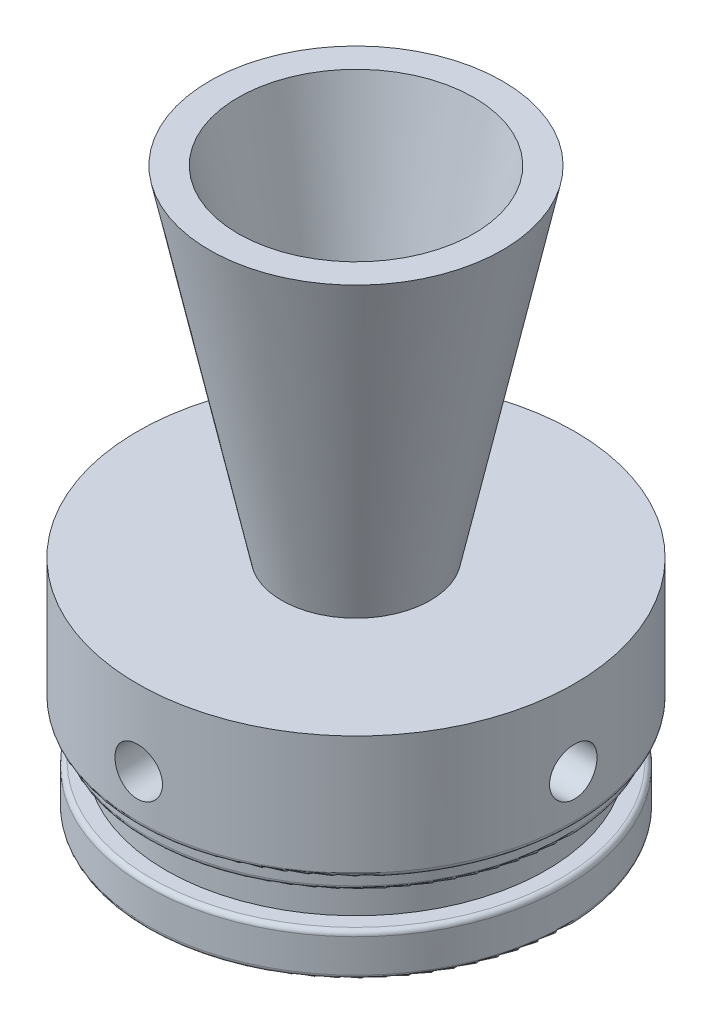
SolidWorks part; units mm, degrees
material "보통 탄소강"
ref_plane "정면" through (0, 0, 0) normal (0, 0, 1) x (1, 0, 0)
ref_plane "윗면" through (0, 0, 0) normal (0, 1, 0) x (1, 0, 0)
ref_plane "우측면" through (0, 0, 0) normal (1, 0, 0) x (0, 0, -1)
sketch "스케치1" plane through (0, 0, 0) normal (0, 0, 1) x (1, 0, 0)
  line L8 (0, 0) -> (0, 58.72)
  line L9 (0, 58.72) -> (12.41, 58.72)
  line L10 (12.41, 58.72) -> (4.605, 21.99)
  line L11 (4.605, 21.99) -> (20, 0)
  line L12 (20, 0) -> (0, 0)
  line L13 (4.605, 21.99) -> (0, 21.99)
  line L14 (0, 0) -> (0, 58.72)
  line L15 (12.41, 58.72) -> (15.41, 58.72)
  line L16 (15.41, 58.72) -> (7.8196, 23)
  line L17 (7.8196, 23) -> (23, 23)
  line L18 (23, 23) -> (23, 10)
  line L19 (23, 10) -> (22, 10)
  line L20 (22, 10) -> (22, 0)
  line L21 (22, 0) -> (20, 0)
  line L22 (22, 10) -> (22, 8)
  line L23 (22, 8) -> (20, 8)
  line L24 (20, 8) -> (20, 4.5)
  line L25 (20, 4.5) -> (22, 4.5)
  line L26 (22, 4.5) -> (22, 0)
  line L27 (20, 0) -> (22, 0)
  line L28 (20, 8) -> (22, 8.175)
  dimension "D1" = 58.72
  dimension "D2" = 4.605
  dimension "D3" = 20
  dimension "D4" = 12.41
  dimension "D5" = 21.99
  dimension "D6" = 3
  dimension "D7" = 2
  dimension "D8" = 1
  dimension "D9" = 10
  dimension "D10" = 13
  dimension "D11" = 2
  dimension "D12" = 2
  dimension "D13" = 3.5
revolve "회전2" add sketch "스케치1" angle 360 about L8
fillet "필렛3" radius 0.5 1 edges at (0, 8.175, -22)
fillet "필렛4" radius 0.5 1 edges at (0, 4.5, -22)
ref_plane "평면1" through (-23, 0, 0) normal (-1, 0, 0) x (0, 0, 1)
sketch "스케치4" plane through (-23, 0, 0) normal (-1, 0, 0) x (0, 0, 1)
  line L0 (0, 10) -> (0, 15)
  line L1 (-22, 10) -> (22, 10) construction
  circle A0 centre (0, 15) radius 2.5
  dimension "D1" = 5
extrude "컷-돌출1" cut sketch "스케치4" against normal blind 6
ref_plane "평면2" through (0, 0, 23) normal (0, 0, 1) x (1, 0, 0)
sketch "스케치5" plane through (0, 0, 23) normal (0, 0, 1) x (1, 0, 0)
  line L0 (0, 10) -> (0, 15)
  line L1 (-22, 10) -> (22, 10) construction
  circle A0 centre (0, 15) radius 2.5
  dimension "D1" = 5
extrude "컷-돌출2" cut sketch "스케치5" against normal blind 6
ref_plane "평면3" through (23, 0, 0) normal (1, 0, 0) x (0, 0, -1)
sketch "스케치6" plane through (23, 0, 0) normal (1, 0, 0) x (0, 0, -1)
  line L0 (0, 10) -> (0, 15)
  line L1 (-22, 10) -> (22, 10) construction
  circle A0 centre (0, 15) radius 2.5
  dimension "D1" = 5
extrude "컷-돌출3" cut sketch "스케치6" against normal blind 6
ref_plane "평면4" through (0, 0, -23) normal (0, 0, -1) x (-1, 0, 0)
sketch "스케치7" plane through (0, 0, -23) normal (0, 0, -1) x (-1, 0, 0)
  line L0 (0, 10) -> (0, 15)
  line L1 (-22, 10) -> (22, 10) construction
  circle A0 centre (0, 15) radius 2.5
  dimension "D1" = 5
extrude "컷-돌출4" cut sketch "스케치7" against normal blind 6
fillet "필렛5" radius 0.5 1 edges at (0, 0, -22)
fillet "필렛6" radius 0.5 1 edges at (0, 10, -23)
